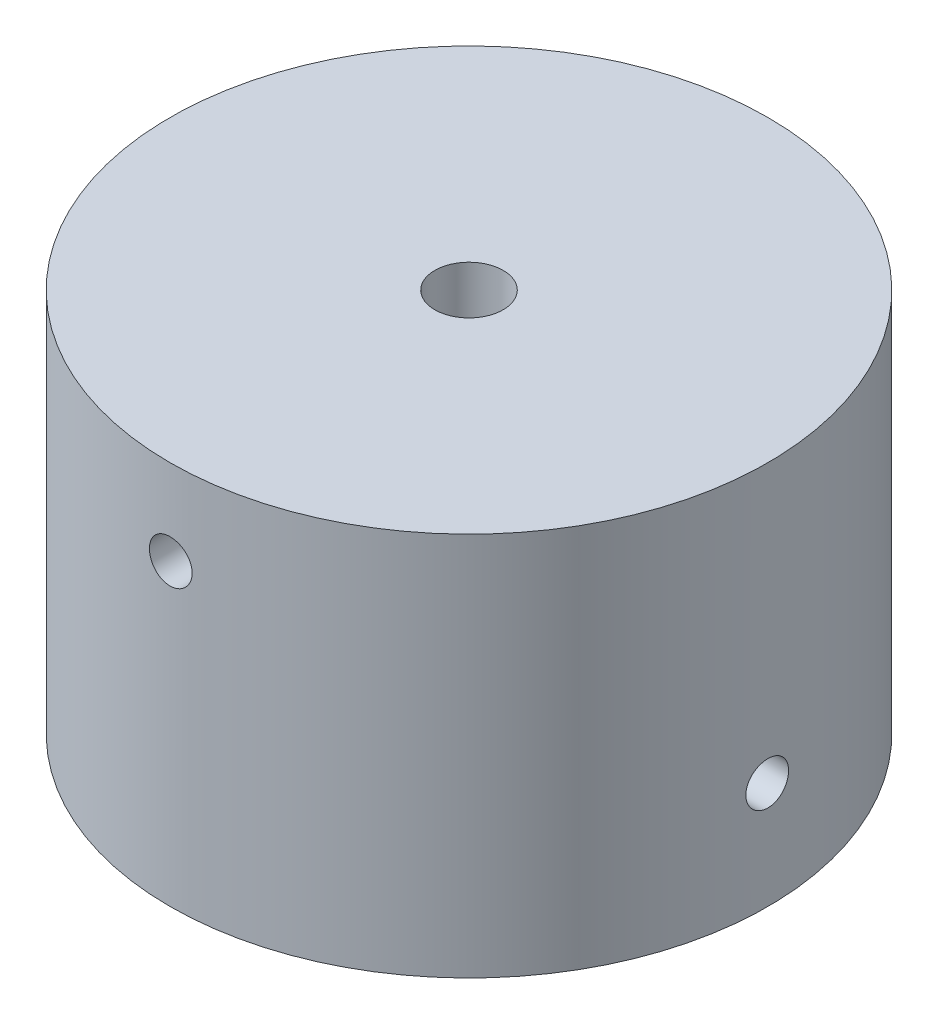
SolidWorks part; units mm, degrees
ref_plane "Front Plane" through (0, 0, 0) normal (0, 0, 1) x (1, 0, 0)
ref_plane "Top Plane" through (0, 0, 0) normal (0, 1, 0) x (1, 0, 0)
ref_plane "Right Plane" through (0, 0, 0) normal (1, 0, 0) x (0, 0, -1)
sketch "Sketch1" plane through (0, 0, 0) normal (0, 1, 0) x (1, 0, 0)
  circle A0 centre (0, 0) radius 14
  dimension "D1" = 28
extrude "Boss-Extrude1" add sketch "Sketch1" along normal blind 18
sketch "Sketch2" plane through (0, 18, 0) normal (0, 1, 0) x (1, 0, 0)
  circle A0 centre (0, 0) radius 1.6
  dimension "D1" = 3.2
extrude "Cut-Extrude1" cut sketch "Sketch2" against normal blind 18
sketch "Sketch3" plane through (0, 0, 0) normal (0, -1, 0) x (1, 0, 0)
  circle A0 centre (0, 0) radius 4
  dimension "D1" = 8
extrude "Cut-Extrude2" cut sketch "Sketch3" against normal blind 10
sketch "Sketch4" plane through (0, 0, 0) normal (1, 0, 0) x (0, 0, -1)
  line L0 (0, 3.5641) -> (0, 16.3046) construction
  circle A1 centre (0, 5) radius 1
  dimension "D2" = 5
  dimension "D1" = 2
extrude "Cut-Extrude3" cut sketch "Sketch4" against normal through all and the other way through all
sketch "Sketch5" plane through (0, 0, 0) normal (0, 0, 1) x (1, 0, 0)
  line L0 (0, -3.0934) -> (0, 19.9303) construction
  line L1 (14, 18) -> (-14, 18) construction
  circle A0 centre (0, 14) radius 1
  point P5 (0, 15.2566)
  dimension "D1" = 2
  dimension "D2" = 4
extrude "Cut-Extrude4" cut sketch "Sketch5" against normal through all and the other way through all
